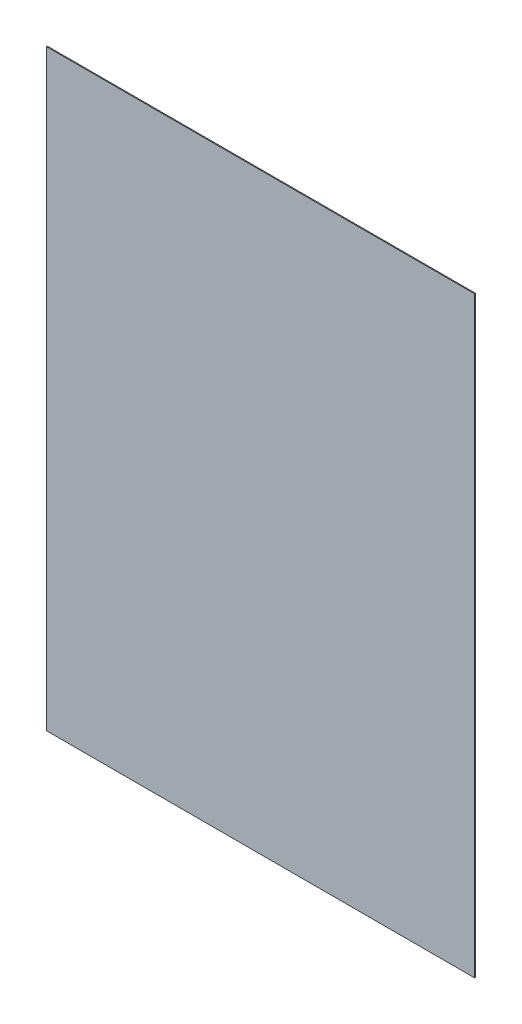
SolidWorks part; units mm, degrees
material "Alloy Steel"
ref_plane "Front Plane" through (0, 0, 0) normal (0, 0, 1) x (1, 0, 0)
ref_plane "Top Plane" through (0, 0, 0) normal (0, 1, 0) x (1, 0, 0)
ref_plane "Right Plane" through (0, 0, 0) normal (1, 0, 0) x (0, 0, -1)
sketch "Sketch1" plane through (0, 0, 0) normal (0, 0, 1) x (1, 0, 0)
  line L1 (-440.0949, 167.9852) -> (29.9051, 167.9852)
  line L2 (-440.0949, 167.9852) -> (-440.0949, -482.0148)
  line L3 (-440.0949, -482.0148) -> (29.9051, -482.0148)
  line L4 (29.9051, 167.9852) -> (29.9051, -482.0148)
  line L5 (-440.0949, 167.9852) -> (29.9051, -482.0148) construction
  line L6 (-440.0949, -482.0148) -> (29.9051, 167.9852) construction
  point P0 (-205.0949, -157.0148)
  dimension "D1" = 470
  dimension "D2" = 650
extrude "Boss-Extrude1" add sketch "Sketch1" along normal blind 1
